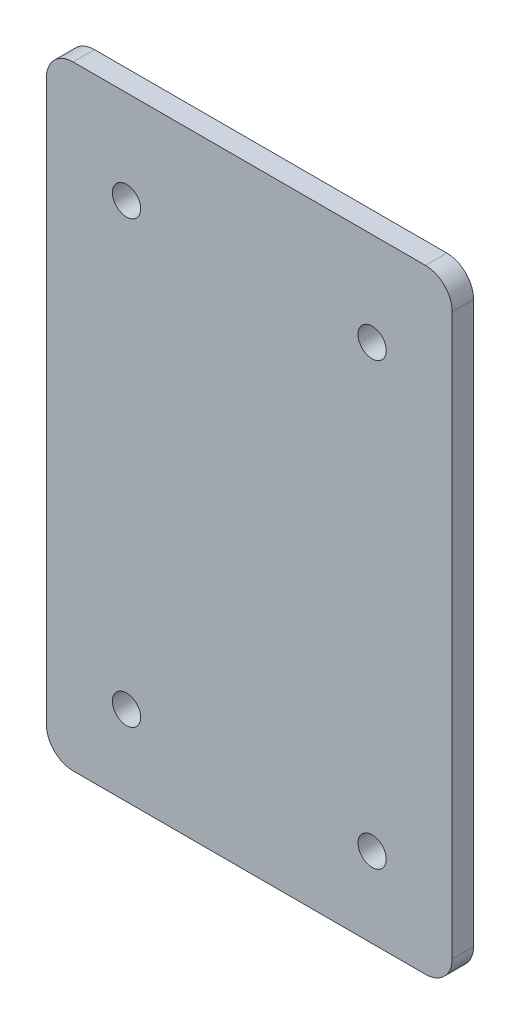
SolidWorks part; units mm, degrees
ref_plane "Front Plane" through (0, 0, 0) normal (0, 0, 1) x (1, 0, 0)
ref_plane "Top Plane" through (0, 0, 0) normal (0, 1, 0) x (1, 0, 0)
ref_plane "Right Plane" through (0, 0, 0) normal (1, 0, 0) x (0, 0, -1)
sketch "Sketch1" plane through (0, 0, 0) normal (0, 0, 1) x (1, 0, 0)
  line L0 (-38, -30) -> (38, -30)
  line L1 (0, -4.4) -> (0, 4.4) construction
  line L3 (38, 85) -> (-38, 85)
  line L6 (4.4, 0) -> (-4.4, 0) construction
  line L8 (-38, 85) -> (-38, -30)
  line L9 (38, 85) -> (38, -30)
  dimension "D1" = 38
  dimension "D3" = 30
  dimension "D5" = 115
  dimension "D7" = 76
extrude "Boss-Extrude1" add sketch "Sketch1" along normal blind 4
hole_wizard "M5 Clearance Hole1" positions "Sketch4" profile "Sketch3" hole size "M5" standard "ISO" end condition through all
sketch "Sketch4" plane through (0, 0, 4) normal (0, 0, 1) x (1, 0, 0)
  line L0 (0, 0) -> (0, 82.324) construction
  line L1 (0, -4.4) -> (0, 4.4) construction
  line L4 (-23, -15) -> (-23, 150)
  point P2 (-23, 67.5)
  point P3 (-23, -15)
  point P17 (23, -15)
  point P19 (23, 67.5)
  dimension "D3" = 23
sketch "Sketch3" plane through (-23, 67.5, 4) normal (1, 0, 0) x (0, -1, 0)
  line L0 (0, 0) -> (0, 4)
  line L1 (0, 4) -> (2.65, 4)
  line L2 (2.65, 4) -> (2.65, 0)
  line L5 (2.65, 0) -> (0, 0)
  line L11 (0, -6.35) -> (0, 107.95) construction
  dimension "Thru Hole Dia." = 5.3
  dimension "Thru Hole Depth" = 4
fillet "Fillet1" radius 5 4 edges at (38, 85, 2) (38, -30, 2) (-38, -30, 2) (-38, 85, 2)
